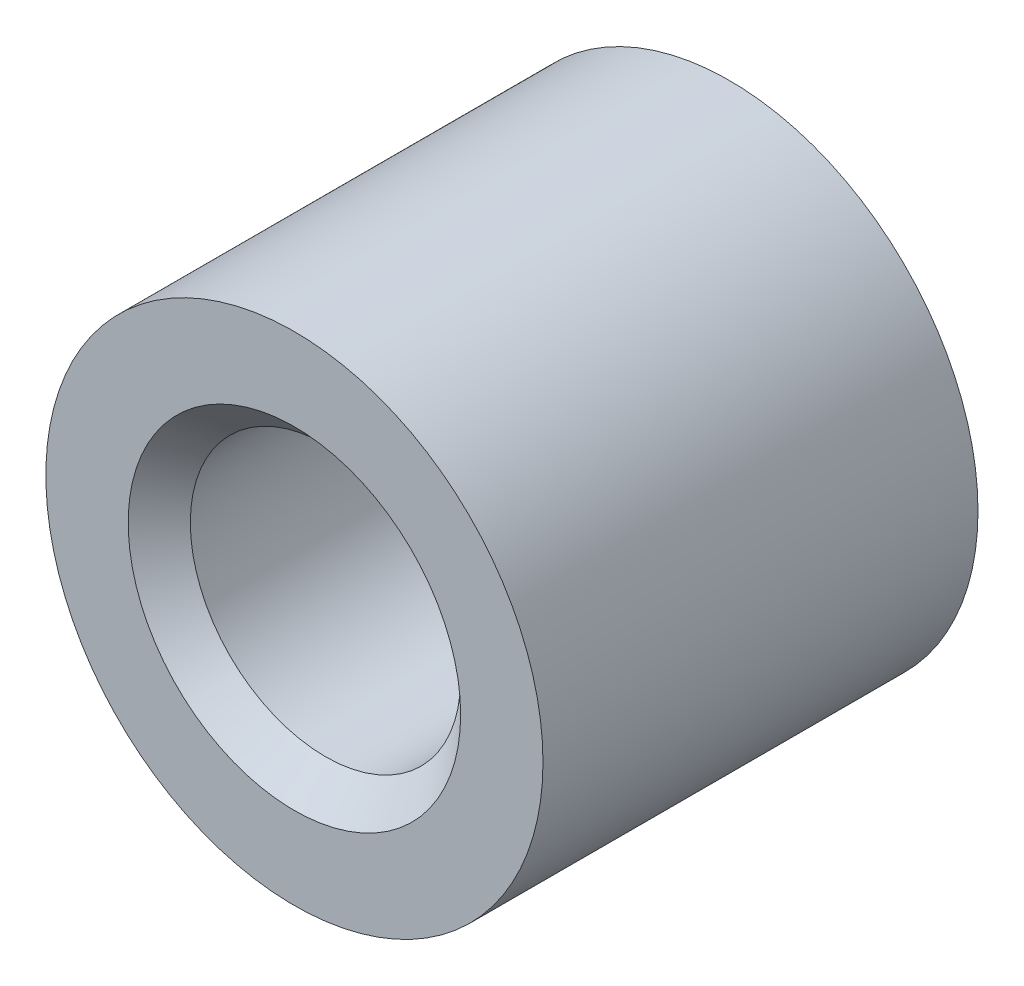
SolidWorks part; units mm, degrees
ref_plane "Front Plane" through (0, 0, 0) normal (0, 0, 1) x (1, 0, 0)
ref_plane "Top Plane" through (0, 0, 0) normal (0, 1, 0) x (1, 0, 0)
ref_plane "Right Plane" through (0, 0, 0) normal (1, 0, 0) x (0, 0, -1)
sketch "Sketch1" plane through (0, 0, 0) normal (0, 0, 1) x (1, 0, 0)
  circle A0 centre (0, 0) radius 4.35
  circle A1 centre (0, 0) radius 8
  dimension "D1" = 8.7
  dimension "D2" = 16
extrude "Boss-Extrude1" add sketch "Sketch1" along normal blind 14
chamfer "Chamfer1" distance 1 angle 45 2 edges at (4.35, 0, 14) (4.35, 0, 0)
